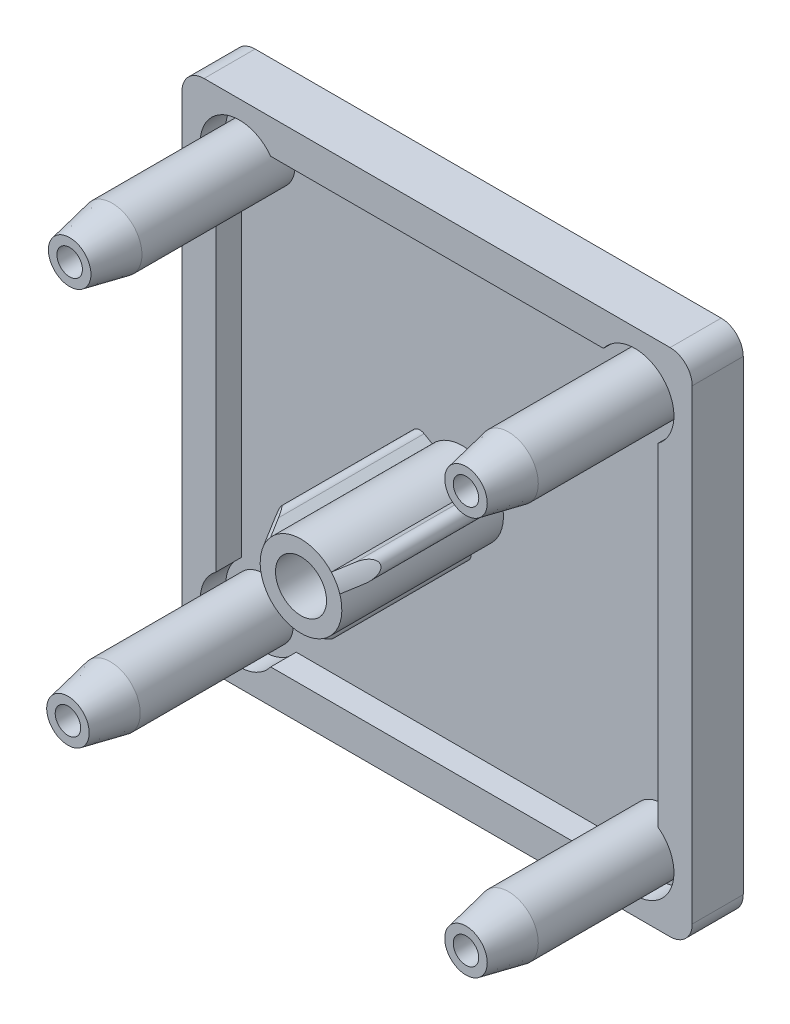
SolidWorks part; units mm, degrees
ref_plane "Front Plane" through (0, 0, 0) normal (0, 0, 1) x (1, 0, 0)
ref_plane "Top Plane" through (0, 0, 0) normal (0, 1, 0) x (1, 0, 0)
ref_plane "Right Plane" through (0, 0, 0) normal (1, 0, 0) x (0, 0, -1)
ref_plane "Plane1" through (0, 0, 0) normal (0, 0, 1) x (1, 0, 0)
sketch "Sketch1" plane through (0, 0, 0) normal (0, 0, 1) x (1, 0, 0)
  line L0 (-15, 13.7) -> (-15, -13.7)
  line L1 (-13.7, -15) -> (13.7, -15)
  line L2 (15, -13.7) -> (15, 13.7)
  line L3 (13.7, 15) -> (-13.7, 15)
  arc A0 (-15, -13.7) -> (-13.7, -15) centre (-13.7, -13.7) ccw
  arc A1 (13.7, -15) -> (15, -13.7) centre (13.7, -13.7) ccw
  arc A2 (15, 13.7) -> (13.7, 15) centre (13.7, 13.7) ccw
  arc A3 (-13.7, 15) -> (-15, 13.7) centre (-13.7, 13.7) ccw
extrude "Boss-Extrude1" add sketch "Sketch1" against normal blind 3
ref_plane "Plane2" through (0, 0, 0) normal (0, 0, 1) x (1, 0, 0)
sketch "Sketch2" plane through (0, 0, 0) normal (0, 0, 1) x (1, 0, 0)
  line L0 (-13, 9.7813) -> (-13, -9.7813)
  line L1 (-9.7813, -13) -> (9.7813, -13)
  line L2 (13, -9.7813) -> (13, 9.7813)
  line L3 (9.7813, 13) -> (-9.7813, 13)
  arc A0 (-9.7813, 13) -> (-13, 9.7813) centre (-11.625, 11.625) ccw
  arc A1 (-13, -9.7813) -> (-9.7813, -13) centre (-11.625, -11.625) ccw
  arc A2 (9.7813, -13) -> (13, -9.7813) centre (11.625, -11.625) ccw
  arc A3 (13, 9.7813) -> (9.7813, 13) centre (11.625, 11.625) ccw
extrude "Cut-Extrude1" cut sketch "Sketch2" against normal blind 1.5
ref_plane "Plane3" through (-11.6, 0, 0) normal (1, 0, 0) x (0, 0, -1)
sketch "Sketch3" plane through (-11.6, 0, 0) normal (1, 0, 0) x (0, 0, -1)
  line L0 (0, 11.7) -> (0, 12.45)
  line L1 (0, 12.45) -> (-10, 12.45)
  line L2 (-10, 12.45) -> (-10, 12.95)
  line L3 (-10, 12.95) -> (-7.5, 13.45)
  line L4 (-7.5, 13.45) -> (1.5, 13.45)
  line L5 (1.5, 13.45) -> (1.5, 11.7)
  line L6 (1.5, 11.7) -> (0, 11.7)
  line L7 (1.5, 11.7) -> (-10, 11.7) construction
revolve "Revolve1" add sketch "Sketch3" angle 360 about L7
ref_plane "Plane4" through (11.7, 0, 0) normal (1, 0, 0) x (0, 0, -1)
sketch "Sketch4" plane through (11.7, 0, 0) normal (1, 0, 0) x (0, 0, -1)
  line L0 (0, 11.7) -> (0, 12.45)
  line L1 (0, 12.45) -> (-10, 12.45)
  line L2 (-10, 12.45) -> (-10, 12.95)
  line L3 (-10, 12.95) -> (-7.5, 13.45)
  line L4 (-7.5, 13.45) -> (1.5, 13.45)
  line L5 (1.5, 13.45) -> (1.5, 11.7)
  line L6 (1.5, 11.7) -> (0, 11.7)
  line L7 (1.5, 11.7) -> (-10, 11.7) construction
revolve "Revolve2" add sketch "Sketch4" angle 360 about L7
ref_plane "Plane5" through (11.7, 0, 0) normal (1, 0, 0) x (0, 0, -1)
sketch "Sketch5" plane through (11.7, 0, 0) normal (1, 0, 0) x (0, 0, -1)
  line L0 (0, -11.7) -> (0, -10.95)
  line L1 (0, -10.95) -> (-10, -10.95)
  line L2 (-10, -10.95) -> (-10, -10.45)
  line L3 (-10, -10.45) -> (-7.5, -9.95)
  line L4 (-7.5, -9.95) -> (1.5, -9.95)
  line L5 (1.5, -9.95) -> (1.5, -11.7)
  line L6 (1.5, -11.7) -> (0, -11.7)
  line L7 (1.5, -11.7) -> (-10, -11.7) construction
revolve "Revolve3" add sketch "Sketch5" angle 360 about L7
ref_plane "Plane6" through (-11.7, 0, 0) normal (1, 0, 0) x (0, 0, -1)
sketch "Sketch6" plane through (-11.7, 0, 0) normal (1, 0, 0) x (0, 0, -1)
  line L0 (0, -11.7) -> (0, -10.95)
  line L1 (0, -10.95) -> (-10, -10.95)
  line L2 (-10, -10.95) -> (-10, -10.45)
  line L3 (-10, -10.45) -> (-7.5, -9.95)
  line L4 (-7.5, -9.95) -> (1.5, -9.95)
  line L5 (1.5, -9.95) -> (1.5, -11.7)
  line L6 (1.5, -11.7) -> (0, -11.7)
  line L7 (1.5, -11.7) -> (-10, -11.7) construction
revolve "Revolve4" add sketch "Sketch6" angle 360 about L7
ref_plane "Plane7" through (0, 0, 0) normal (1, 0, 0) x (0, 0, -1)
sketch "Sketch7" plane through (0, 0, 0) normal (1, 0, 0) x (0, 0, -1)
  line L0 (-8, 1.5) -> (1.5, 1.5)
  line L1 (1.5, 1.5) -> (1.5, 3.4)
  line L2 (1.5, 3.4) -> (-6.2679, 3.4)
  line L3 (-6.2679, 3.4) -> (-8, 2.4)
  line L4 (-8, 2.4) -> (-8, 1.5)
  line L5 (10, 0) -> (-10, 0) construction
revolve "Revolve5" add sketch "Sketch7" angle 360 about L5
ref_plane "Plane8" through (0, 0, -1.5) normal (0, 0, 1) x (1, 0, 0)
sketch "Sketch8" plane through (0, 0, -1.5) normal (0, 0, 1) x (1, 0, 0)
  line L0 (-2.7615, 1.017) -> (-2.2829, 0.7407)
  line L1 (-0.5, -2.3473) -> (-0.5, -2.9)
  line L2 (0.5, -2.9) -> (0.5, -2.3473)
  line L3 (2.2829, 0.7407) -> (2.7615, 1.017)
  line L4 (2.2615, 1.883) -> (1.7829, 1.6067)
  line L5 (-1.7829, 1.6067) -> (-2.2615, 1.883)
  circle A0 centre (0, 0) radius 6
  arc A1 (-2.2615, 1.883) -> (-2.7615, 1.017) centre (-2.5115, 1.45) ccw
  arc A2 (-2.2829, 0.7407) -> (-0.5, -2.3473) centre (0, 0) ccw
  arc A3 (-0.5, -2.9) -> (0.5, -2.9) centre (0, -2.9) ccw
  arc A4 (0.5, -2.3473) -> (2.2829, 0.7407) centre (0, 0) ccw
  arc A5 (2.7615, 1.017) -> (2.2615, 1.883) centre (2.5115, 1.45) ccw
  arc A6 (1.7829, 1.6067) -> (-1.7829, 1.6067) centre (0, 0) ccw
extrude "Cut-Extrude2" cut sketch "Sketch8" along normal blind 10
